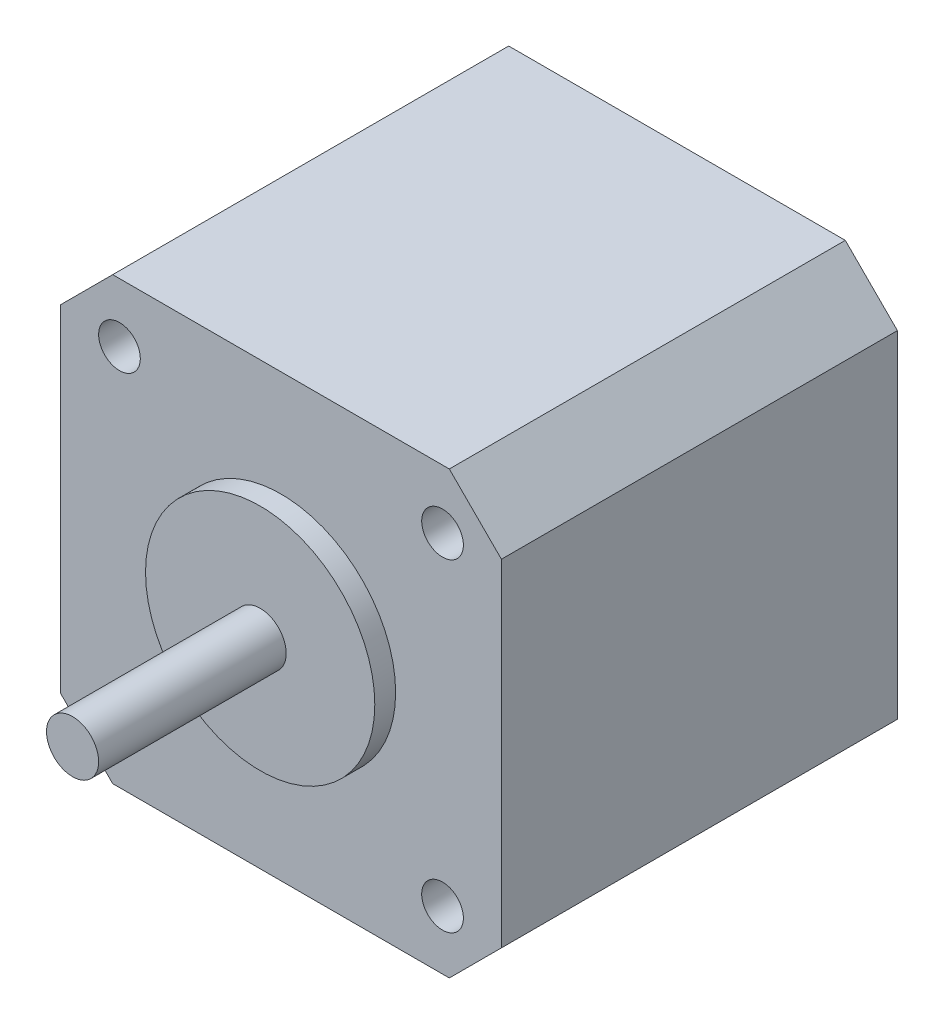
SolidWorks part; units mm, degrees
ref_plane "Ön Düzlem" through (0, 0, 0) normal (0, 0, 1) x (1, 0, 0)
ref_plane "Üst Düzlem" through (0, 0, 0) normal (0, 1, 0) x (1, 0, 0)
ref_plane "Sağ Düzlem" through (0, 0, 0) normal (1, 0, 0) x (0, 0, -1)
sketch "Çizim1" plane through (0, 0, 0) normal (0, 0, 1) x (1, 0, 0)
  line L1 (21.15, -21.15) -> (-21.15, -21.15)
  line L2 (21.15, -21.15) -> (21.15, 21.15)
  line L3 (21.15, 21.15) -> (-21.15, 21.15)
  line L4 (-21.15, -21.15) -> (-21.15, 21.15)
  line L5 (21.15, -21.15) -> (-21.15, 21.15) construction
  line L6 (21.15, 21.15) -> (-21.15, -21.15) construction
  point P0 (0, 0)
  dimension "D1" = 42.3
  dimension "D2" = 42.3
extrude "Yükseklik-Ekstrüzyon1" add sketch "Çizim1" along normal blind 38 contours L3 L4 L1 L2
chamfer "Pah1" distance 5 angle 45 4 edges at (21.15, -21.15, 19) (-21.15, -21.15, 19) (-21.15, 21.15, 19) (21.15, 21.15, 19)
sketch "Çizim2" plane through (0, 0, 38) normal (0, 0, 1) x (1, 0, 0)
  circle A0 centre (-15.5, 15.5) radius 2
  circle A1 centre (15.5, 15.5) radius 2
  circle A2 centre (-15.5, -15.5) radius 2
  circle A3 centre (15.5, -15.5) radius 2
  dimension "D1" = 4
  dimension "D2" = 31
  dimension "D3" = 31
  dimension "D4" = 15.5
  dimension "D5" = 15.5
extrude "Kes-Ekstrüzyon1" cut sketch "Çizim2" against normal blind 5
sketch "Çizim3" plane through (0, 0, 38) normal (0, 0, 1) x (1, 0, 0)
  circle A0 centre (0, 0) radius 11
  dimension "D1" = 22
extrude "Yükseklik-Ekstrüzyon2" add sketch "Çizim3" along normal blind 2
sketch "Çizim4" plane through (0, 0, 40) normal (0, 0, 1) x (1, 0, 0)
  circle A0 centre (0, 0) radius 2.5
  dimension "D1" = 5
extrude "Yükseklik-Ekstrüzyon3" add sketch "Çizim4" along normal blind 18
